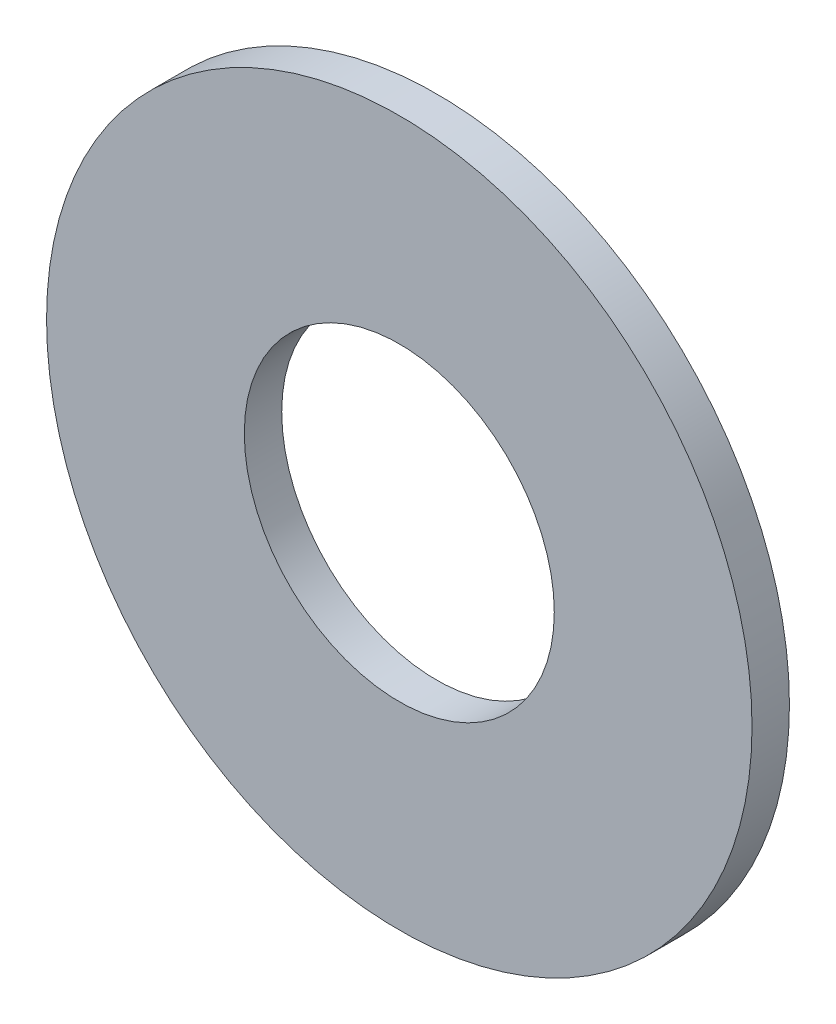
SolidWorks part; units mm, degrees
material "AISI 1020"
ref_plane "前视基准面" through (0, 0, 0) normal (0, 0, 1) x (1, 0, 0)
ref_plane "上视基准面" through (0, 0, 0) normal (0, 1, 0) x (1, 0, 0)
ref_plane "右视基准面" through (0, 0, 0) normal (1, 0, 0) x (0, 0, -1)
sketch "草图1" plane through (0, 0, 0) normal (0, 0, 1) x (1, 0, 0)
  circle A0 centre (0, 0) radius 33
  circle A1 centre (0, 0) radius 14.5
  dimension "D1" = 29
  dimension "D2" = 66
extrude "凸台-拉伸1" add sketch "草图1" along normal mid plane 3.5
